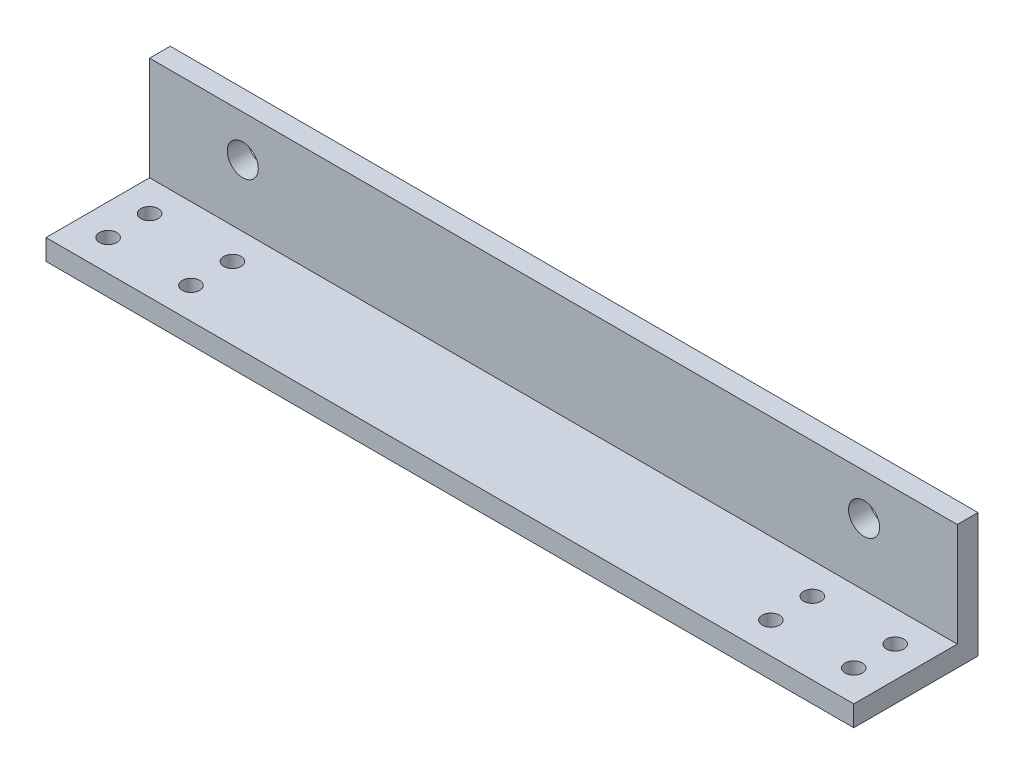
SolidWorks part; units mm, degrees
material "6063-O"
ref_plane "Front Plane" through (0, 0, 0) normal (0, 0, 1) x (1, 0, 0)
ref_plane "Top Plane" through (0, 0, 0) normal (0, 1, 0) x (1, 0, 0)
ref_plane "Right Plane" through (0, 0, 0) normal (1, 0, 0) x (0, 0, -1)
sketch "Sketch1" plane through (0, 0, 0) normal (1, 0, 0) x (0, 0, -1)
  line L0 (-38.1, 0) -> (0, 0)
  line L1 (55, 0) -> (-55, 0) construction
  line L2 (0, 0) -> (0, 38.1)
  line L3 (0, 55) -> (0, -55) construction
  dimension "D1" = 38.1
  dimension "D2" = 38.1
extrude "Extrude-Thin1" add sketch "Sketch1" along normal mid plane 247.65 thin thin type one direction reverse wall 6.35
hole_wizard "#10 Clearance Hole1" positions "Sketch2" profile "Sketch3" hole size "#10" standard "ANSI Inch" end condition up to next
sketch "Sketch2" plane through (0, 6.35, 0) normal (0, 1, 0) x (1, 0, 0)
  line L0 (123.825, -38.1) -> (-123.825, -38.1) construction
  line L1 (0, -20.955) -> (0, 20.955) construction
  point P0 (-114.3, -15.875)
  point P2 (-114.3, -28.575)
  point P4 (-88.9, -28.575)
  point P6 (-88.9, -15.875)
  point P8 (88.9, -15.875)
  point P10 (88.9, -28.575)
  point P12 (114.3, -28.575)
  point P14 (114.3, -15.875)
  dimension "D1" = 9.525
  dimension "D2" = 12.7
  dimension "D3" = 114.3
  dimension "D4" = 25.4
  dimension "D5" = 114.3
  dimension "D6" = 25.4
sketch "Sketch3" plane through (-114.3, 6.35, 15.875) normal (1, 0, 0) x (0, 0, 1)
  line L0 (0, 0) -> (0, 6.35)
  line L1 (0, 6.35) -> (2.667, 6.35)
  line L2 (2.667, 6.35) -> (2.667, 0)
  line L5 (2.667, 0) -> (0, 0)
  line L11 (0, -6.35) -> (0, 107.95) construction
  dimension "Thru Hole Dia." = 5.334
  dimension "Thru Hole Depth" = 6.35
hole_wizard "3/8 (0.375) Diameter Hole1" positions "Sketch4" profile "Sketch5" hole size "3/8" standard "ANSI Inch" end condition up to next
sketch "Sketch4" plane through (0, 0, 6.35) normal (0, 0, 1) x (1, 0, 0)
  line L0 (123.825, 38.1) -> (-123.825, 38.1) construction
  line L1 (0, -20.955) -> (0, 20.955) construction
  point P0 (-95.25, 25.4)
  point P2 (95.25, 25.4)
  dimension "D1" = 12.7
  dimension "D2" = 190.5
  dimension "D3" = 95.25
sketch "Sketch5" plane through (-95.25, 25.4, 6.35) normal (1, 0, 0) x (0, -1, 0)
  line L0 (0, 0) -> (0, 6.35)
  line L1 (0, 6.35) -> (4.7625, 6.35)
  line L2 (4.7625, 6.35) -> (4.7625, 0)
  line L5 (4.7625, 0) -> (0, 0)
  line L11 (0, -6.35) -> (0, 107.95) construction
  dimension "Thru Hole Dia." = 9.525
  dimension "Thru Hole Depth" = 6.35
